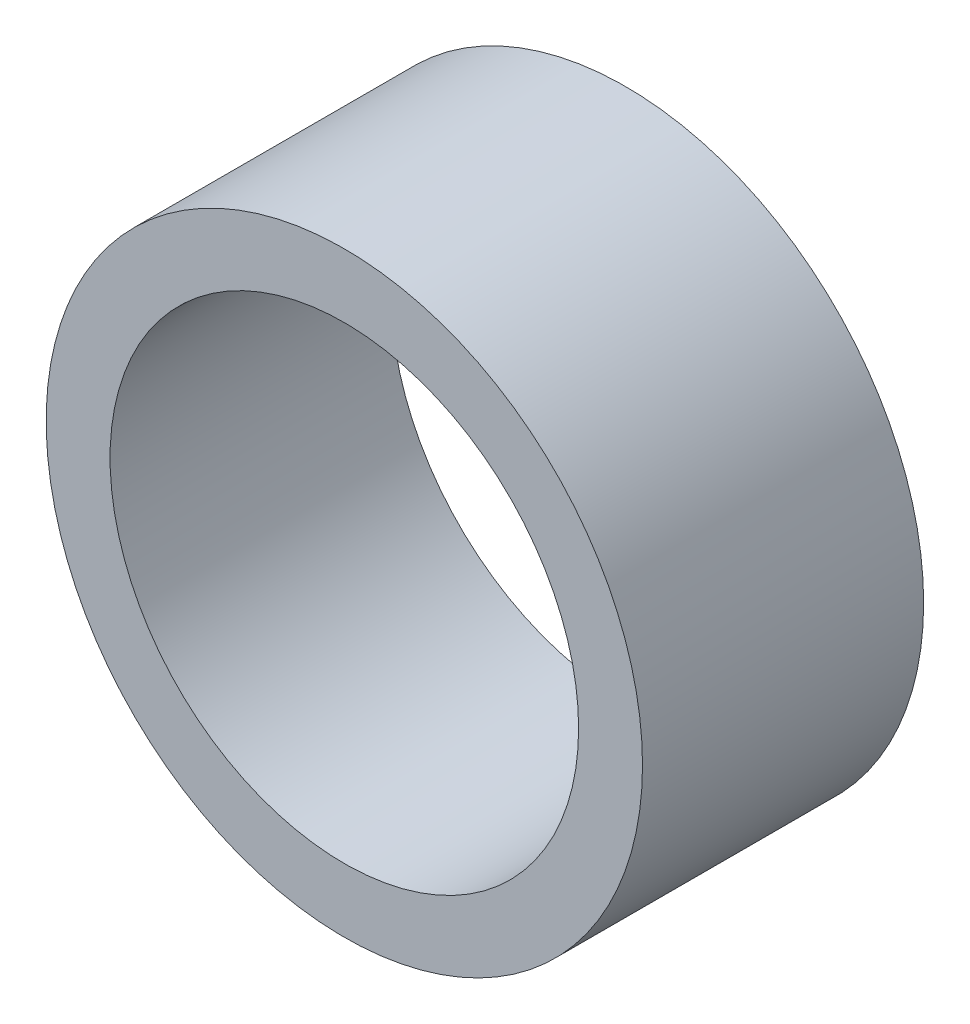
SolidWorks part; units mm, degrees
ref_plane "Płaszczyzna przednia" through (0, 0, 0) normal (0, 0, 1) x (1, 0, 0)
ref_plane "Płaszczyzna górna" through (0, 0, 0) normal (0, 1, 0) x (1, 0, 0)
ref_plane "Płaszczyzna prawa" through (0, 0, 0) normal (1, 0, 0) x (0, 0, -1)
sketch "Szkic1" plane through (0, 0, 0) normal (0, 0, 1) x (1, 0, 0)
  circle A0 centre (0, 0) radius 11
  circle A1 centre (0, 0) radius 14
  dimension "D1" = 22
  dimension "D2" = 3
extrude "Dodanie-wyciągnięcie1" add sketch "Szkic1" along normal blind 13.2
